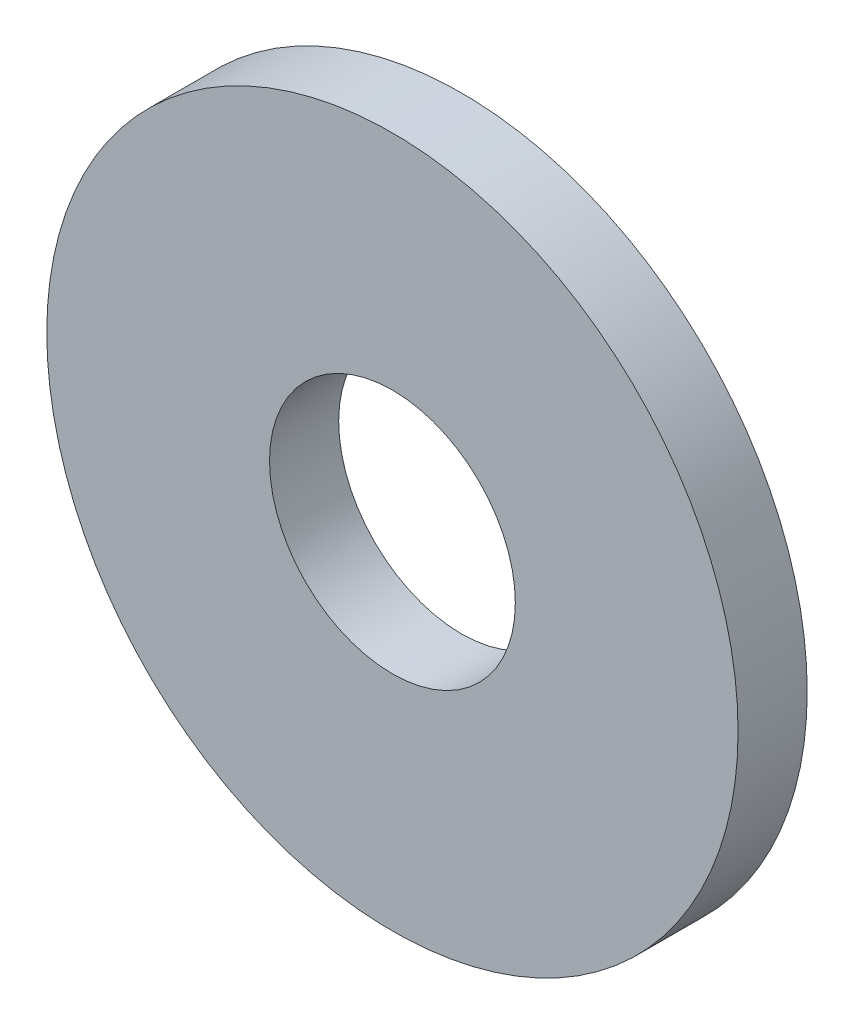
SolidWorks part; units mm, degrees
ref_plane "Front Plane" through (0, 0, 0) normal (0, 0, 1) x (1, 0, 0)
ref_plane "Top Plane" through (0, 0, 0) normal (0, 1, 0) x (1, 0, 0)
ref_plane "Right Plane" through (0, 0, 0) normal (1, 0, 0) x (0, 0, -1)
sketch "Sketch1" plane through (0, 0, 0) normal (0, 0, 1) x (1, 0, 0)
  circle A0 centre (0, 0) radius 9
  circle A1 centre (0, 0) radius 3.2
  dimension "OD" = 18
  dimension "ID1" = 6.4
extrude "Boss-Extrude1" add sketch "Sketch1" along normal blind 1.8
